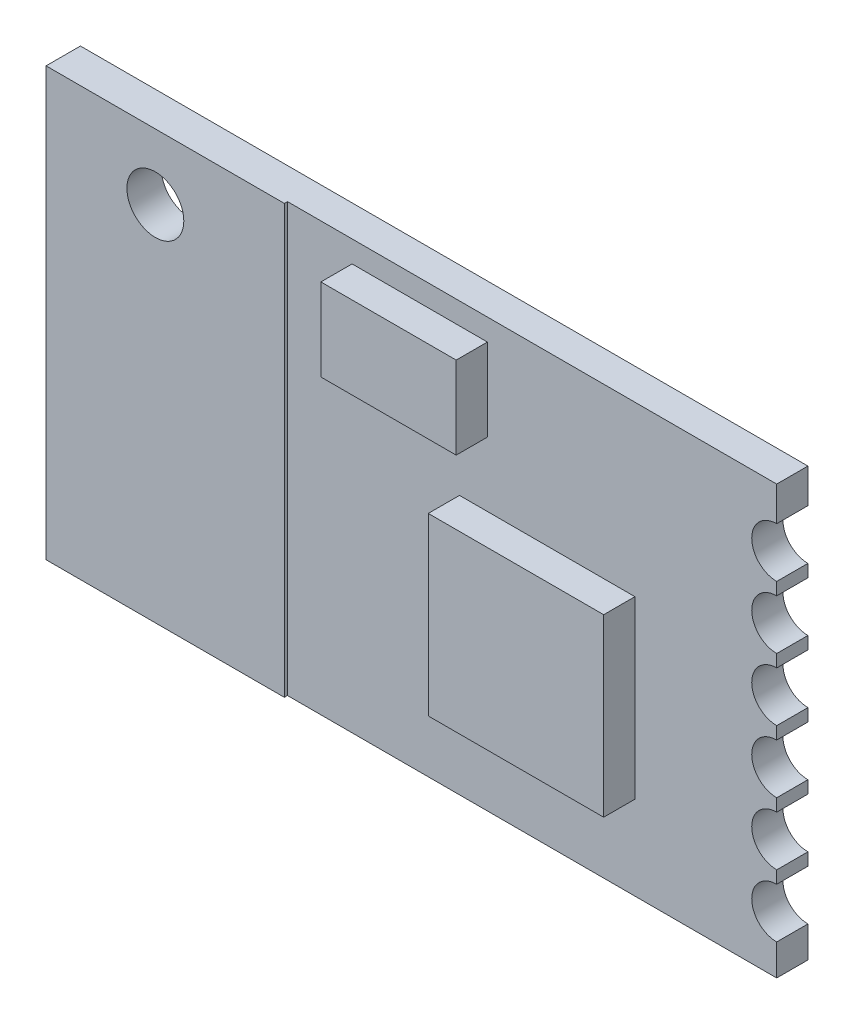
SolidWorks part; units mm, degrees
ref_plane "Front Plane" through (0, 0, 0) normal (0, 0, 1) x (1, 0, 0)
ref_plane "Top Plane" through (0, 0, 0) normal (0, 1, 0) x (1, 0, 0)
ref_plane "Right Plane" through (0, 0, 0) normal (1, 0, 0) x (0, 0, -1)
sketch "Sketch1" plane through (0, 0, 0) normal (0, 0, 1) x (1, 0, 0)
  line L0 (23.3, -2.7) -> (23.3, -3.1)
  line L5 (0, 0) -> (23.3, 0)
  line L6 (0, 0) -> (0, -13.7)
  line L7 (0, -13.7) -> (23.3, -13.7)
  line L8 (23.3, 0) -> (23.3, -1.1)
  line L9 (23.3, -4.7) -> (23.3, -5.1)
  line L10 (23.3, -6.7) -> (23.3, -7.1)
  line L11 (23.3, -8.7) -> (23.3, -9.1)
  line L12 (23.3, -10.7) -> (23.3, -11.1)
  line L13 (23.3, -12.7) -> (23.3, -13.7)
  circle A0 centre (3.5, -2.1) radius 0.9111
  arc A1 (23.3, -1.1) -> (23.3, -2.7) centre (23.3, -1.9) ccw
  arc A2 (23.3, -3.1) -> (23.3, -4.7) centre (23.3, -3.9) ccw
  arc A3 (23.3, -5.1) -> (23.3, -6.7) centre (23.3, -5.9) ccw
  arc A4 (23.3, -7.1) -> (23.3, -8.7) centre (23.3, -7.9) ccw
  arc A5 (23.3, -9.1) -> (23.3, -10.7) centre (23.3, -9.9) ccw
  arc A6 (23.3, -11.1) -> (23.3, -12.7) centre (23.3, -11.9) ccw
  dimension "D5" = 1.9
  dimension "D1" = 23.3
  dimension "D2" = 13.7
  dimension "D3" = 2.1
  dimension "D4" = 3.5
  dimension "D6" = 2
  dimension "D7" = 2
  dimension "D8" = 2
  dimension "D9" = 2
  dimension "D10" = 2
extrude "Boss-Extrude1" add sketch "Sketch1" along normal blind 1
sketch "Sketch2" plane through (0, 0, 1) normal (0, 0, 1) x (1, 0, 0)
  line L0 (0, -13.7) -> (23.3, -13.7) construction
  line L1 (0, 0) -> (7.6315, 0)
  line L2 (0, 0) -> (0, -13.7)
  line L3 (0, -13.7) -> (7.6315, -13.7)
  line L4 (7.6315, 0) -> (7.6315, -13.7)
  circle A1 centre (3.5, -2.1) radius 0.9111
  circle A2 centre (2.9548, -2.8259) radius 0.0033
  line M5 (0, 0) -> (0, -13.7)
  line M6 (0, -13.7) -> (23.3, -13.7)
  line M20 (23.3, 0) -> (0, 0)
  circle M21 centre (3.5, -2.1) radius 0.9111
extrude "Boss-Extrude2" add sketch "Sketch2" along normal blind 0.1 contours L4 M20 M5 M6 M21
sketch "Sketch3" plane through (0, 0, 0) normal (0, 0, 1) x (1, 0, 0)
  line L1 (13.1404, -5.3939) -> (18.7583, -5.3939)
  line L2 (13.1404, -5.3939) -> (13.1404, -11.0118)
  line L3 (13.1404, -11.0118) -> (18.7583, -11.0118)
  line L4 (18.7583, -5.3939) -> (18.7583, -11.0118)
  line L5 (9.701, -0.6933) -> (14.0347, -0.6933)
  line L6 (9.701, -0.6933) -> (9.701, -3.3303)
  line L7 (9.701, -3.3303) -> (14.0347, -3.3303)
  line L8 (14.0347, -0.6933) -> (14.0347, -3.3303)
extrude "Boss-Extrude3" add sketch "Sketch3" along normal blind 2
